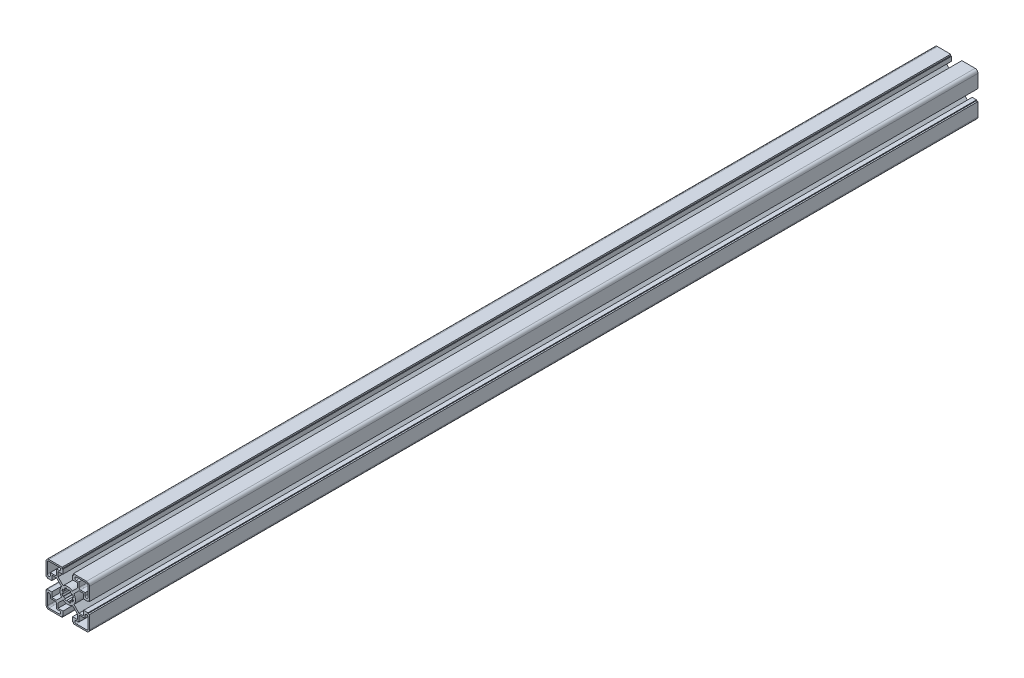
SolidWorks part; units mm, degrees
ref_plane "Front Plane" through (0, 0, 0) normal (0, 0, 1) x (1, 0, 0)
ref_plane "Top Plane" through (0, 0, 0) normal (0, 1, 0) x (1, 0, 0)
ref_plane "Right Plane" through (0, 0, 0) normal (1, 0, 0) x (0, 0, -1)
sketch "Sketch1" plane through (0, 0, 0) normal (0, 0, 1) x (1, 0, 0)
  line L2 (-19.5072, 22.5044) -> (-5.7912, 22.5044)
  line L3 (-5.7912, 22.5044) -> (-5.7912, 21.0058)
  line L4 (-5.7912, 21.0058) -> (-5.0038, 21.0058)
  line L6 (-5.0038, 21.0058) -> (-5.0038, 16.51)
  line L7 (-5.0038, 16.51) -> (-10.0457, 16.51)
  line L8 (-10.0457, 16.51) -> (-10.0457, 11.6801)
  line L9 (-10.0457, 11.6801) -> (-4.781, 6.4154)
  line L11 (-11.6801, 10.0457) -> (-6.4154, 4.781)
  line L12 (-16.51, 10.0457) -> (-11.6801, 10.0457)
  line L13 (-16.51, 5.0038) -> (-16.51, 10.0457)
  line L14 (-21.0058, 5.0038) -> (-16.51, 5.0038)
  line L15 (-21.0058, 5.7912) -> (-21.0058, 5.0038)
  line L16 (-22.5044, 5.7912) -> (-21.0058, 5.7912)
  line L17 (-22.5044, 19.5072) -> (-22.5044, 5.7912)
  line L18 (-18.0086, 11.5443) -> (-13.0429, 11.5443)
  line L19 (-18.0086, 11.5443) -> (-18.0086, 8.7884)
  line L20 (-11.5443, 18.0086) -> (-11.5443, 13.0429)
  line L21 (-21.0058, 19.5072) -> (-21.0058, 8.7884)
  line L23 (-11.5443, 18.0086) -> (-8.7884, 18.0086)
  line L24 (-19.5072, 21.0058) -> (-8.7884, 21.0058)
  line L25 (1.1893, 5.9789) -> (0.9762, 4.9077)
  line L26 (-1.1893, 5.9789) -> (-0.9762, 4.9077)
  line L27 (5.0686, 3.3868) -> (4.1605, 2.78)
  line L28 (3.3868, 5.0686) -> (2.78, 4.1605)
  line L29 (5.9789, -1.1893) -> (4.9077, -0.9762)
  line L30 (5.9789, 1.1893) -> (4.9077, 0.9762)
  line L31 (3.3868, -5.0686) -> (2.78, -4.1605)
  line L32 (5.0686, -3.3868) -> (4.1605, -2.78)
  line L33 (-1.1893, -5.9789) -> (-0.9762, -4.9077)
  line L34 (1.1893, -5.9789) -> (0.9762, -4.9077)
  line L35 (-5.0686, -3.3868) -> (-4.1605, -2.78)
  line L36 (-3.3868, -5.0686) -> (-2.78, -4.1605)
  line L37 (-5.9789, 1.1893) -> (-4.9077, 0.9762)
  line L38 (-5.9789, -1.1893) -> (-4.9077, -0.9762)
  line L39 (-3.3868, 5.0686) -> (-2.78, 4.1605)
  line L40 (-5.0686, 3.3868) -> (-4.1605, 2.78)
  line L41 (11.5443, 18.0086) -> (8.7884, 18.0086)
  line L42 (19.5072, 21.0058) -> (8.7884, 21.0058)
  line L43 (19.5072, 22.5044) -> (5.7912, 22.5044)
  line L44 (5.7912, 22.5044) -> (5.7912, 21.0058)
  line L45 (5.7912, 21.0058) -> (5.0038, 21.0058)
  line L46 (5.0038, 21.0058) -> (5.0038, 16.51)
  line L47 (5.0038, 16.51) -> (10.0457, 16.51)
  line L48 (10.0457, 16.51) -> (10.0457, 11.6801)
  line L49 (10.0457, 11.6801) -> (4.781, 6.4154)
  line L50 (11.6801, 10.0457) -> (6.4154, 4.781)
  line L51 (21.0058, 19.5072) -> (21.0058, 8.7884)
  line L52 (11.5443, 18.0086) -> (11.5443, 13.0429)
  line L53 (18.0086, 11.5443) -> (18.0086, 8.7884)
  line L54 (18.0086, 11.5443) -> (13.0429, 11.5443)
  line L55 (22.5044, 19.5072) -> (22.5044, 5.7912)
  line L56 (22.5044, 5.7912) -> (21.0058, 5.7912)
  line L57 (21.0058, 5.7912) -> (21.0058, 5.0038)
  line L58 (21.0058, 5.0038) -> (16.51, 5.0038)
  line L59 (16.51, 5.0038) -> (16.51, 10.0457)
  line L60 (16.51, 10.0457) -> (11.6801, 10.0457)
  line L61 (16.51, -10.0457) -> (11.6801, -10.0457)
  line L62 (16.51, -5.0038) -> (16.51, -10.0457)
  line L63 (21.0058, -5.0038) -> (16.51, -5.0038)
  line L64 (21.0058, -5.7912) -> (21.0058, -5.0038)
  line L65 (22.5044, -5.7912) -> (21.0058, -5.7912)
  line L66 (22.5044, -19.5072) -> (22.5044, -5.7912)
  line L67 (18.0086, -11.5443) -> (13.0429, -11.5443)
  line L68 (18.0086, -11.5443) -> (18.0086, -8.7884)
  line L69 (11.5443, -18.0086) -> (11.5443, -13.0429)
  line L70 (21.0058, -19.5072) -> (21.0058, -8.7884)
  line L71 (11.6801, -10.0457) -> (6.4154, -4.781)
  line L72 (10.0457, -11.6801) -> (4.781, -6.4154)
  line L73 (10.0457, -16.51) -> (10.0457, -11.6801)
  line L74 (5.0038, -16.51) -> (10.0457, -16.51)
  line L75 (5.0038, -21.0058) -> (5.0038, -16.51)
  line L76 (5.7912, -21.0058) -> (5.0038, -21.0058)
  line L77 (5.7912, -22.5044) -> (5.7912, -21.0058)
  line L78 (19.5072, -22.5044) -> (5.7912, -22.5044)
  line L79 (19.5072, -21.0058) -> (8.7884, -21.0058)
  line L80 (11.5443, -18.0086) -> (8.7884, -18.0086)
  line L81 (-11.5443, -18.0086) -> (-8.7884, -18.0086)
  line L82 (-19.5072, -21.0058) -> (-8.7884, -21.0058)
  line L83 (-19.5072, -22.5044) -> (-5.7912, -22.5044)
  line L84 (-5.7912, -22.5044) -> (-5.7912, -21.0058)
  line L85 (-5.7912, -21.0058) -> (-5.0038, -21.0058)
  line L86 (-5.0038, -21.0058) -> (-5.0038, -16.51)
  line L87 (-5.0038, -16.51) -> (-10.0457, -16.51)
  line L88 (-10.0457, -16.51) -> (-10.0457, -11.6801)
  line L89 (-10.0457, -11.6801) -> (-4.781, -6.4154)
  line L90 (-11.6801, -10.0457) -> (-6.4154, -4.781)
  line L91 (-21.0058, -19.5072) -> (-21.0058, -8.7884)
  line L92 (-11.5443, -18.0086) -> (-11.5443, -13.0429)
  line L93 (-18.0086, -11.5443) -> (-18.0086, -8.7884)
  line L94 (-18.0086, -11.5443) -> (-13.0429, -11.5443)
  line L95 (-22.5044, -19.5072) -> (-22.5044, -5.7912)
  line L96 (-22.5044, -5.7912) -> (-21.0058, -5.7912)
  line L97 (-21.0058, -5.7912) -> (-21.0058, -5.0038)
  line L98 (-21.0058, -5.0038) -> (-16.51, -5.0038)
  line L99 (-16.51, -5.0038) -> (-16.51, -10.0457)
  line L100 (-16.51, -10.0457) -> (-11.6801, -10.0457)
  arc A0 (-22.5044, 19.5072) -> (-19.5072, 22.5044) centre (-19.5072, 19.5072) cw
  arc A1 (-21.0058, 8.7884) -> (-18.0086, 8.7884) centre (-19.5072, 8.7884) ccw
  arc A2 (-21.0058, 19.5072) -> (-19.5072, 21.0058) centre (-19.5072, 19.5072) cw
  arc A3 (-8.7884, 21.0058) -> (-8.7884, 18.0086) centre (-8.7884, 19.5072) cw
  arc A4 (-11.5443, 13.0429) -> (-13.0429, 11.5443) centre (-13.0429, 13.0429) cw
  arc A5 (6.4154, -4.781) -> (6.4154, 4.781) centre (0, 0) ccw
  arc A6 (0.9762, 4.9077) -> (-0.9762, 4.9077) centre (0, 0) ccw
  arc A7 (-5.0686, 3.3868) -> (-5.9789, 1.1893) centre (0, 0) ccw
  arc A8 (4.1605, 2.78) -> (2.78, 4.1605) centre (0, 0) ccw
  arc A9 (4.9077, -0.9762) -> (4.9077, 0.9762) centre (0, 0) ccw
  arc A10 (2.78, -4.1605) -> (4.1605, -2.78) centre (0, 0) ccw
  arc A11 (-0.9762, -4.9077) -> (0.9762, -4.9077) centre (0, 0) ccw
  arc A12 (-4.1605, -2.78) -> (-2.78, -4.1605) centre (0, 0) ccw
  arc A13 (-4.9077, 0.9762) -> (-4.9077, -0.9762) centre (0, 0) ccw
  arc A14 (-2.78, 4.1605) -> (-4.1605, 2.78) centre (0, 0) ccw
  arc A15 (-5.9789, -1.1893) -> (-5.0686, -3.3868) centre (0, 0) ccw
  arc A16 (-3.3868, -5.0686) -> (-1.1893, -5.9789) centre (0, 0) ccw
  arc A17 (1.1893, -5.9789) -> (3.3868, -5.0686) centre (0, 0) ccw
  arc A18 (5.0686, -3.3868) -> (5.9789, -1.1893) centre (0, 0) ccw
  arc A19 (5.9789, 1.1893) -> (5.0686, 3.3868) centre (0, 0) ccw
  arc A20 (3.3868, 5.0686) -> (1.1893, 5.9789) centre (0, 0) ccw
  arc A21 (-1.1893, 5.9789) -> (-3.3868, 5.0686) centre (0, 0) ccw
  arc A22 (8.7884, 21.0058) -> (8.7884, 18.0086) centre (8.7884, 19.5072) ccw
  arc A23 (21.0058, 19.5072) -> (19.5072, 21.0058) centre (19.5072, 19.5072) ccw
  arc A24 (22.5044, 19.5072) -> (19.5072, 22.5044) centre (19.5072, 19.5072) ccw
  arc A25 (11.5443, 13.0429) -> (13.0429, 11.5443) centre (13.0429, 13.0429) ccw
  arc A26 (21.0058, 8.7884) -> (18.0086, 8.7884) centre (19.5072, 8.7884) cw
  arc A27 (21.0058, -8.7884) -> (18.0086, -8.7884) centre (19.5072, -8.7884) ccw
  arc A28 (11.5443, -13.0429) -> (13.0429, -11.5443) centre (13.0429, -13.0429) cw
  arc A29 (22.5044, -19.5072) -> (19.5072, -22.5044) centre (19.5072, -19.5072) cw
  arc A30 (21.0058, -19.5072) -> (19.5072, -21.0058) centre (19.5072, -19.5072) cw
  arc A31 (8.7884, -21.0058) -> (8.7884, -18.0086) centre (8.7884, -19.5072) cw
  arc A32 (-8.7884, -21.0058) -> (-8.7884, -18.0086) centre (-8.7884, -19.5072) ccw
  arc A33 (-21.0058, -19.5072) -> (-19.5072, -21.0058) centre (-19.5072, -19.5072) ccw
  arc A34 (-22.5044, -19.5072) -> (-19.5072, -22.5044) centre (-19.5072, -19.5072) ccw
  arc A35 (-11.5443, -13.0429) -> (-13.0429, -11.5443) centre (-13.0429, -13.0429) ccw
  arc A36 (-21.0058, -8.7884) -> (-18.0086, -8.7884) centre (-19.5072, -8.7884) cw
  arc A37 (4.781, 6.4154) -> (-4.781, 6.4154) centre (0, 0) ccw
  arc A38 (-4.781, -6.4154) -> (4.781, -6.4154) centre (0, 0) ccw
  arc A39 (-6.4154, 4.781) -> (-6.4154, -4.781) centre (0, 0) ccw
extrude "Boss-Extrude1" add sketch "Sketch1" along normal mid plane 920
